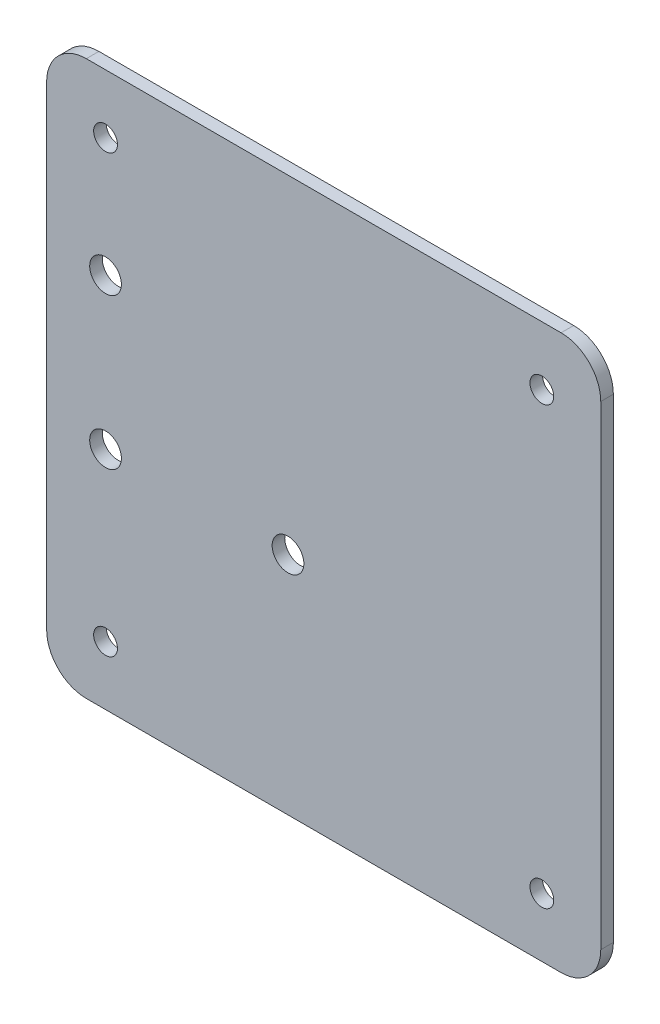
SolidWorks part; units mm, degrees
material "6061-T6 (SS)"
ref_plane "Front Plane" through (0, 0, 0) normal (0, 0, 1) x (1, 0, 0)
ref_plane "Top Plane" through (0, 0, 0) normal (0, 1, 0) x (1, 0, 0)
ref_plane "Right Plane" through (0, 0, 0) normal (1, 0, 0) x (0, 0, -1)
sketch "Sketch1" plane through (0, 0, 0) normal (0, 0, 1) x (1, 0, 0)
  line L1 (66.6353, 1721.56) -> (186.3353, 1721.56)
  line L2 (56.6353, 1711.56) -> (56.6353, 1591.86)
  line L3 (66.6353, 1581.86) -> (186.3353, 1581.86)
  line L4 (196.3353, 1711.56) -> (196.3353, 1591.86)
  line L5 (-97.883, 1661.0458) -> (174.117, 1661.0458) construction
  arc A0 (56.6353, 1591.86) -> (66.6353, 1581.86) centre (66.6353, 1591.86) ccw
  arc A1 (186.3353, 1581.86) -> (196.3353, 1591.86) centre (186.3353, 1591.86) ccw
  arc A2 (186.3353, 1721.56) -> (196.3353, 1711.56) centre (186.3353, 1711.56) cw
  arc A3 (66.6353, 1721.56) -> (56.6353, 1711.56) centre (66.6353, 1711.56) ccw
  point P4 (0, 0)
  point P5 (0, 0)
  point P10 (56.6353, 1581.86)
  point P13 (196.3353, 1581.86)
  point P21 (0, 0)
  dimension "D2" = 10
  dimension "D1" = 139.7
  dimension "D4" = 35
extrude "Boss-Extrude1" add sketch "Sketch1" along normal blind 3.175
sketch "Sketch2" plane through (0, 0, 0) normal (0, 0, -1) x (-1, 0, 0)
  line L0 (-71.4853, 1626.1374) -> (-71.4853, 1679.6302) construction
  line L1 (-117.4853, 1626.1374) -> (-117.4853, 1673.5664) construction
  line L2 (-71.4853, 1638.71) -> (-117.4853, 1638.71) construction
  line L3 (97.883, 1661.0458) -> (-207.117, 1661.0458) construction
  line L4 (-207.117, 1669.0458) -> (-207.117, 1653.0458) construction
  line L5 (-66.6353, 1581.86) -> (-186.3353, 1581.86) construction
  line L13 (-196.3353, 1651.71) -> (-56.6353, 1651.71) construction
  line L14 (-196.3353, 1591.86) -> (-196.3353, 1711.56) construction
  line L15 (-56.6353, 1711.56) -> (-56.6353, 1591.86) construction
  line L16 (-186.3353, 1721.56) -> (-66.6353, 1721.56) construction
  line L21 (-71.4853, 1596.71) -> (-71.4853, 1706.71) construction
  line L22 (-181.4853, 1596.71) -> (-71.4853, 1596.71) construction
  line L23 (-181.4853, 1706.71) -> (-181.4853, 1596.71) construction
  line L24 (-71.4853, 1706.71) -> (-181.4853, 1706.71) construction
  line L25 (-126.4853, 1721.56) -> (-126.4853, 1581.86) construction
  line L26 (-66.6353, 1581.86) -> (-186.3353, 1581.86) construction
  circle A3 centre (-71.4853, 1638.71) radius 4
  circle A4 centre (-71.4853, 1676.71) radius 4
  circle A5 centre (-117.4853, 1638.71) radius 4
  circle A6 centre (-181.4853, 1706.71) radius 3
  circle A7 centre (-71.4853, 1706.71) radius 3
  circle A8 centre (-181.4853, 1596.71) radius 3
  circle A9 centre (-71.4853, 1596.71) radius 3
  dimension "D1" = 8
  dimension "D3" = 6
  dimension "D4" = 15.6642
  dimension "D5" = 22.3358
  dimension "D6" = 9
  dimension "D7" = 46
  dimension "D8" = 55
  dimension "D2" = 55
  dimension "D9" = 55
  dimension "D10" = 55
  dimension "D11" = 79.1858
  dimension "D12" = 56.85
extrude "Cut-Extrude1" cut sketch "Sketch2" against normal through all
